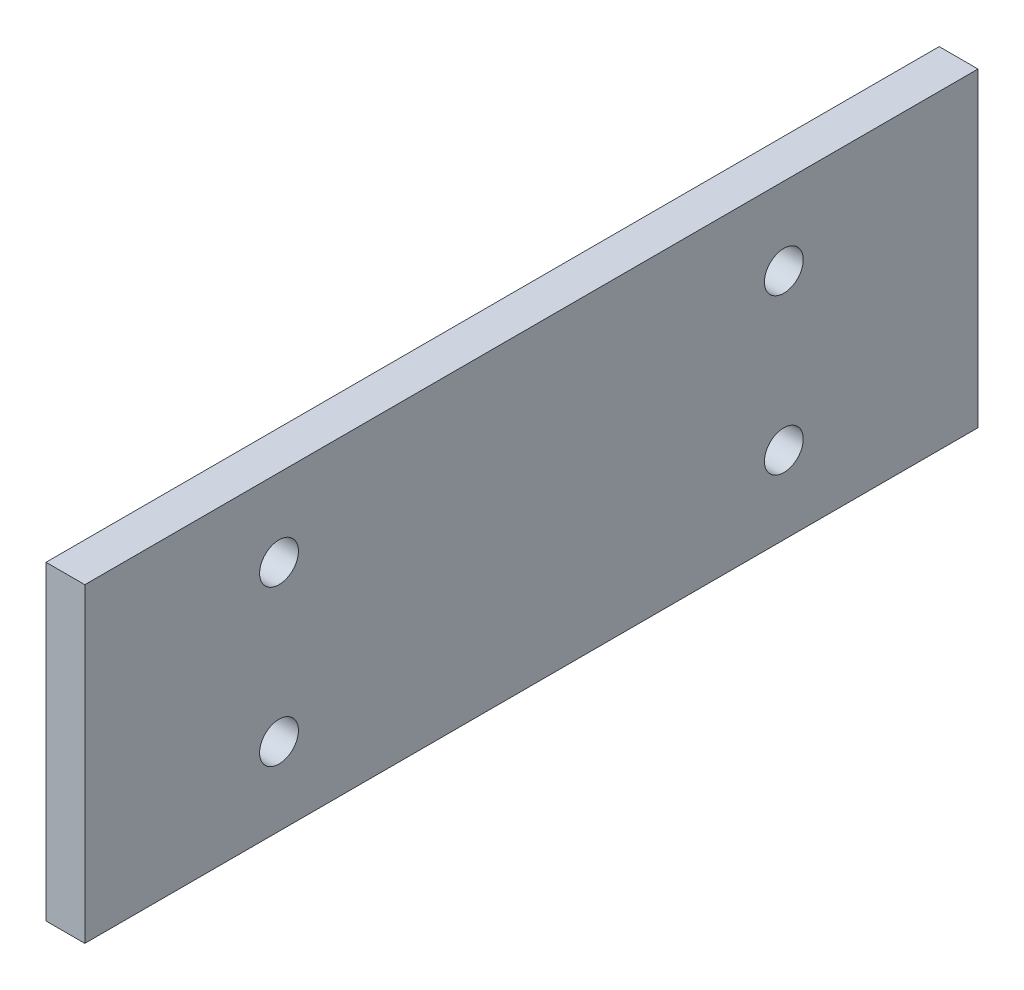
SolidWorks part; units mm, degrees
ref_plane "Ön Düzlem" through (0, 0, 0) normal (0, 0, 1) x (1, 0, 0)
ref_plane "Üst Düzlem" through (0, 0, 0) normal (0, 1, 0) x (1, 0, 0)
ref_plane "Sağ Düzlem" through (0, 0, 0) normal (1, 0, 0) x (0, 0, -1)
sketch "Çizim1" plane through (0, 0, 0) normal (1, 0, 0) x (0, 0, -1)
  line L0 (-57.5, 40) -> (-57.5, -7.1413) construction
  line L1 (0, 0) -> (-115, 0)
  line L2 (0, 0) -> (0, 40)
  line L3 (0, 40) -> (-115, 40)
  line L4 (-115, 0) -> (-115, 40)
  circle A0 centre (-90, 30) radius 2.5
  circle A1 centre (-90, 10) radius 2.5
  circle A2 centre (-25, 10) radius 2.5
  circle A3 centre (-25, 30) radius 2.5
  dimension "D3" = 5
  dimension "D4" = 5
  dimension "D1" = 115
  dimension "D2" = 40
  dimension "D5" = 25
  dimension "D6" = 10
  dimension "D7" = 20
  dimension "D8" = 25
extrude "Yükseklik-Ekstrüzyon1" add sketch "Çizim1" along normal blind 5
